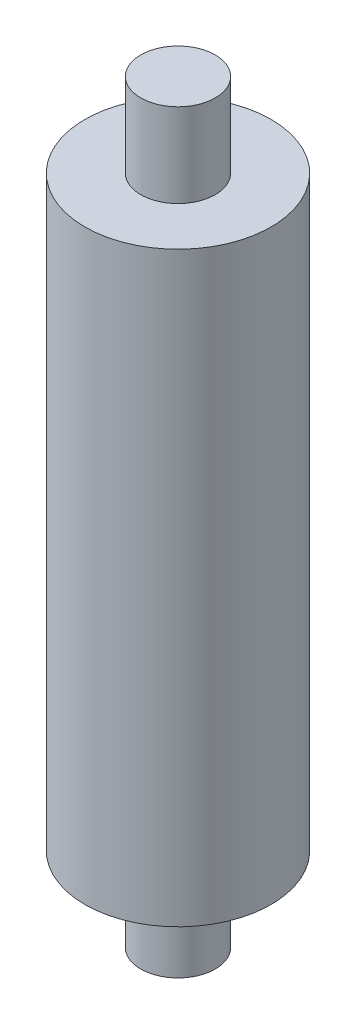
SolidWorks part; units mm, degrees
material "3.3549 (EN-AW 5182)"
ref_plane "Спереди" through (0, 0, 0) normal (0, 0, 1) x (1, 0, 0)
ref_plane "Сверху" through (0, 0, 0) normal (0, 1, 0) x (1, 0, 0)
ref_plane "Справа" through (0, 0, 0) normal (1, 0, 0) x (0, 0, -1)
sketch "Эскиз1" plane through (0, 0, 0) normal (1, 0, 0) x (0, 0, -1)
  line L0 (0, 0) -> (0, -40.5)
  line L1 (0, -40.5) -> (4, -40.5)
  line L2 (4, -40.5) -> (4, -31.5)
  line L3 (4, -31.5) -> (10, -31.5)
  line L4 (10, -31.5) -> (10, 0)
  line L5 (-59.243, 0) -> (-12.757, 0) construction
  line L6 (10, 0) -> (0, 0)
  line L7 (0, -1000) -> (0, 49000) construction
  line L8 (0, -36.5) -> (10, -36.5) construction
  line L9 (10, -33.5) -> (0, -33.5) construction
  dimension "D1" = 4
  dimension "D2" = 2
  dimension "D3" = 8
  dimension "D4" = 20
revolve "Повернуть1" add sketch "Эскиз1" angle 360 about L7
mirror "Зеркальное отражение1" about plane through (0, 0, -10) normal (0, 1, 0) of "Повернуть1"
